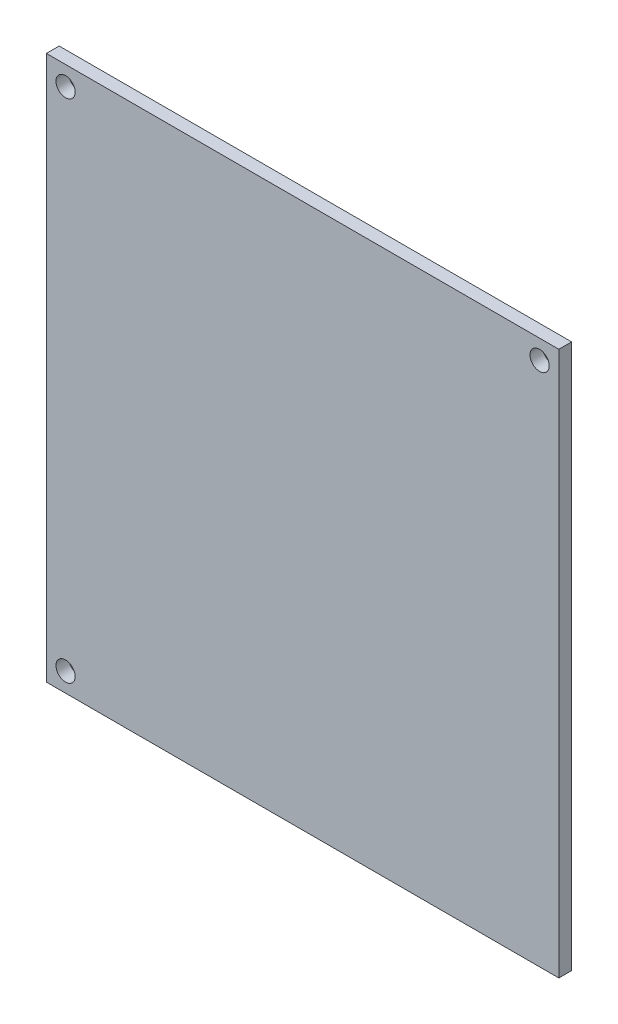
SolidWorks part; units mm, degrees
ref_plane "Ön Düzlem" through (0, 0, 0) normal (0, 0, 1) x (1, 0, 0)
ref_plane "Üst Düzlem" through (0, 0, 0) normal (0, 1, 0) x (1, 0, 0)
ref_plane "Sağ Düzlem" through (0, 0, 0) normal (1, 0, 0) x (0, 0, -1)
sketch "Çizim1" plane through (0, 0, 0) normal (0, 0, 1) x (1, 0, 0)
  line L1 (0, 0) -> (80, 0)
  line L2 (0, 0) -> (0, 85)
  line L3 (0, 85) -> (80, 85)
  line L4 (80, 0) -> (80, 85)
  circle A0 centre (3, 3) radius 1.5
  circle A2 centre (77, 82) radius 1.5
  circle A3 centre (3, 82) radius 1.5
  dimension "D3" = 3
  dimension "D7" = 3
  dimension "D9" = 3
  dimension "D1" = 85
  dimension "D2" = 80
  dimension "D4" = 3
  dimension "D5" = 3
  dimension "D6" = 3
  dimension "D8" = 3
  dimension "D10" = 3
  dimension "D11" = 3
extrude "Yükseklik-Ekstrüzyon1" add sketch "Çizim1" along normal blind 2
